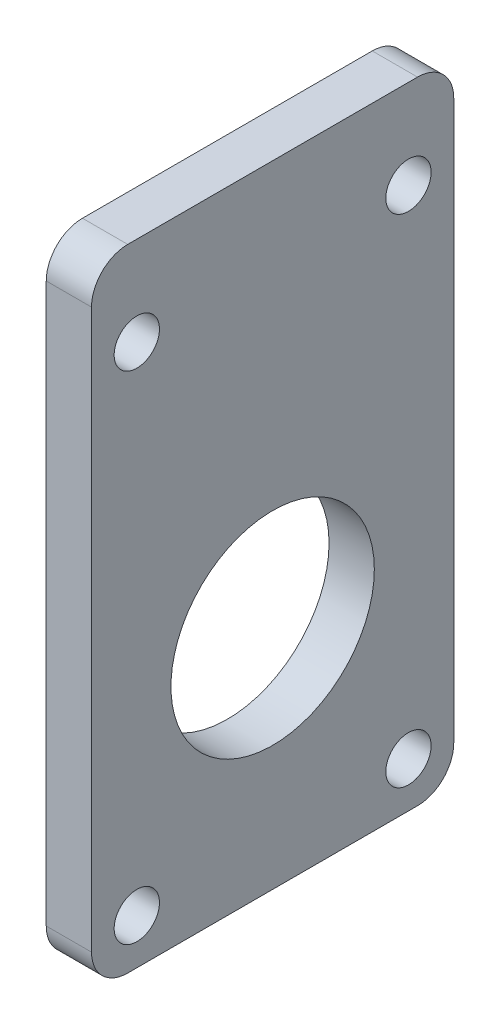
SolidWorks part; units mm, degrees
material "6061-T6 (SS)"
ref_plane "Front Plane" through (0, 0, 0) normal (0, 0, 1) x (1, 0, 0)
ref_plane "Top Plane" through (0, 0, 0) normal (0, 1, 0) x (1, 0, 0)
ref_plane "Right Plane" through (0, 0, 0) normal (1, 0, 0) x (0, 0, -1)
sketch "Sketch1" plane through (0, 0, 0) normal (1, 0, 0) x (0, 0, -1)
  line L0 (-25.4, -12.5) -> (25.4, -12.5) construction
  line L1 (-25.4, -44.25) -> (25.4, -44.25)
  line L2 (-25.4, -44.25) -> (-25.4, 44.25)
  line L3 (-25.4, 44.25) -> (25.4, 44.25)
  line L4 (25.4, -44.25) -> (25.4, 44.25)
  line L5 (-25.4, -44.25) -> (25.4, 44.25) construction
  line L6 (-25.4, 44.25) -> (25.4, -44.25) construction
  line L7 (-25.4, 31.75) -> (25.4, 31.75) construction
  circle A0 centre (0, -12.5) radius 14.2621
  point P0 (0, 0)
  dimension "D4" = 28.5242
  dimension "D1" = 88.5
  dimension "D2" = 50.8
  dimension "D3" = 31.75
  dimension "D5" = 12.5
extrude "Boss-Extrude1" add sketch "Sketch1" along normal mid plane 6.35
fillet "Fillet1" radius 5.08 4 edges at (0, -44.25, -25.4) (0, -44.25, 25.4) (0, 44.25, -25.4) (0, 44.25, 25.4)
hole_wizard "1/4 (0.25) Diameter Hole2" positions "3DSketch2" profile "Sketch3" hole size "1/4" standard "ANSI Inch" end condition through all
sketch3d "3DSketch2"
  line L6 (3.175, 44.25, -20.32) -> (3.175, 44.25, 20.32) construction
  line L7 (3.175, -39.17, -25.4) -> (3.175, 39.17, -25.4) construction
  line L8 (3.175, -44.25, 20.32) -> (3.175, -44.25, -20.32) construction
  line L9 (3.175, 39.17, 25.4) -> (3.175, -39.17, 25.4) construction
  point P0 (3.175, -37.9, 19.05)
  point P2 (3.175, -37.9, -19.05)
  point P10 (3.175, 31.75, 19.05)
  point P12 (3.175, 31.75, -19.05)
  dimension "D1" = 6.35
  dimension "D2" = 6.35
  dimension "D3" = 6.35
  dimension "D4" = 12.5
sketch "Sketch3" plane through (3.175, -37.9, 19.05) normal (0, 1, 0) x (0, 0, -1)
  line L0 (0, 0) -> (0, 6.35)
  line L1 (0, 6.35) -> (3.175, 6.35)
  line L2 (3.175, 6.35) -> (3.175, 0)
  line L5 (3.175, 0) -> (0, 0)
  line L11 (0, -6.35) -> (0, 107.95) construction
  dimension "Thru Hole Dia." = 6.35
  dimension "Thru Hole Depth" = 6.35
